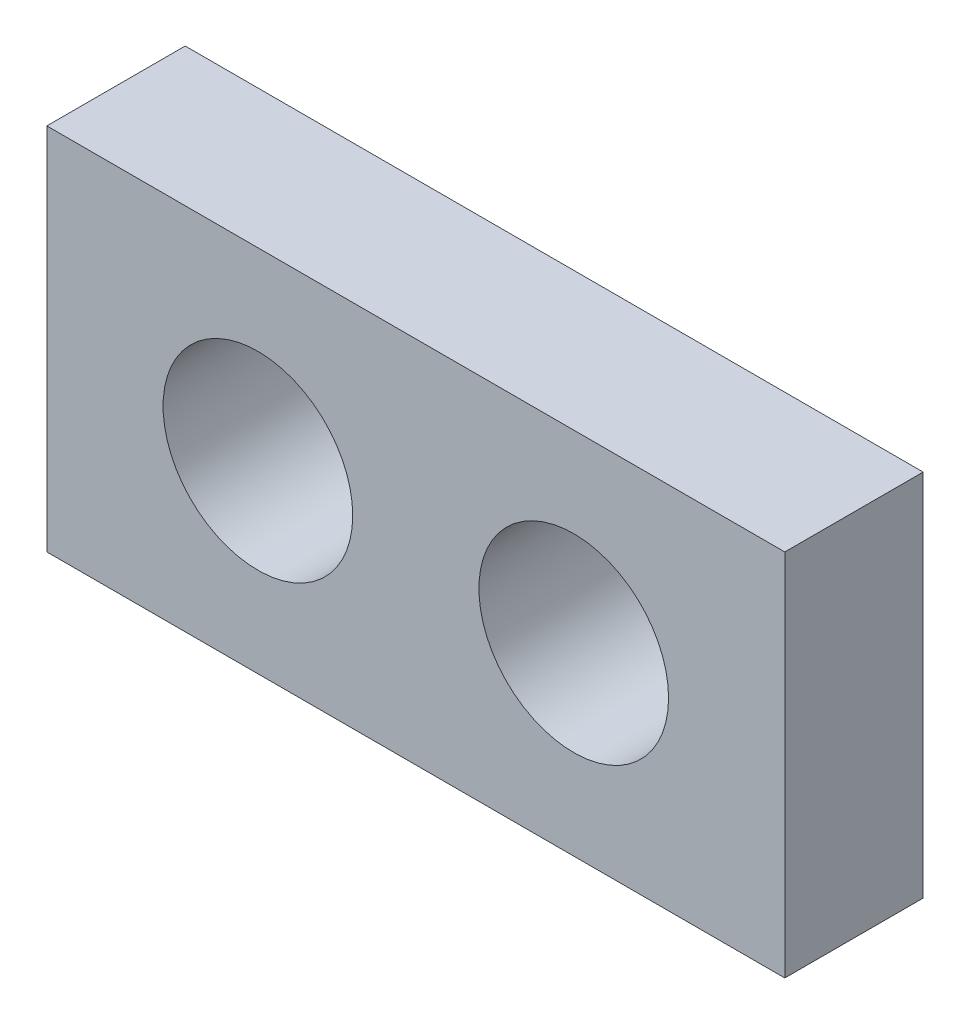
SolidWorks part; units mm, degrees
ref_plane "Front Plane" through (0, 0, 0) normal (0, 0, 1) x (1, 0, 0)
ref_plane "Top Plane" through (0, 0, 0) normal (0, 1, 0) x (1, 0, 0)
ref_plane "Right Plane" through (0, 0, 0) normal (1, 0, 0) x (0, 0, -1)
sketch "Sketch1" plane through (0, 0, 0) normal (0, 0, 1) x (1, 0, 0)
  line L0 (-12.7, -6.35) -> (12.7, -6.35)
  line L1 (-12.7, -6.35) -> (-12.7, 6.35)
  line L2 (12.7, -6.35) -> (12.7, 6.35)
  line L3 (-12.7, 6.35) -> (12.7, 6.35)
  line L4 (-12.7, -6.35) -> (12.7, 6.35) construction
  line L5 (12.7, -6.35) -> (-12.7, 6.35) construction
  point P1 (0, 0)
extrude "Extrude1" add sketch "Sketch1" along normal blind 4.7625
sketch "Sketch2" plane through (0, 0, 4.7625) normal (0, 0, 1) x (1, 0, 0)
  line L0 (0, 0) -> (5.4356, 0) construction
  line L2 (0, 0) -> (-5.4356, 0) construction
hole_wizard "F (0.257) Diameter Hole1" positions "3DSketch2" profile "Sketch4" hole size "F" standard "Ansi Inch"
sketch3d "3DSketch2"
  point P9 (-5.4356, 0, 4.7625)
  point P12 (5.4356, 0, 4.7625)
sketch "Sketch4" plane through (-5.4356, 0, 4.7625) normal (1, 0, 0) x (0, -1, 0)
  line L0 (0, 0) -> (0, 14.6611)
  line L1 (0, 14.6611) -> (3.2639, 12.7)
  line L2 (3.2639, 12.7) -> (3.2639, 0)
  line L5 (3.2639, 0) -> (0, 0)
  line L10 (0, 14.6611) -> (-3.2639, 12.7) construction
  line L11 (0, -6.35) -> (0, 107.95) construction
  dimension "Hole Dia." = 6.5278
  dimension "Hole Depth" = 12.7
  dimension "Drill Angle" = 118
